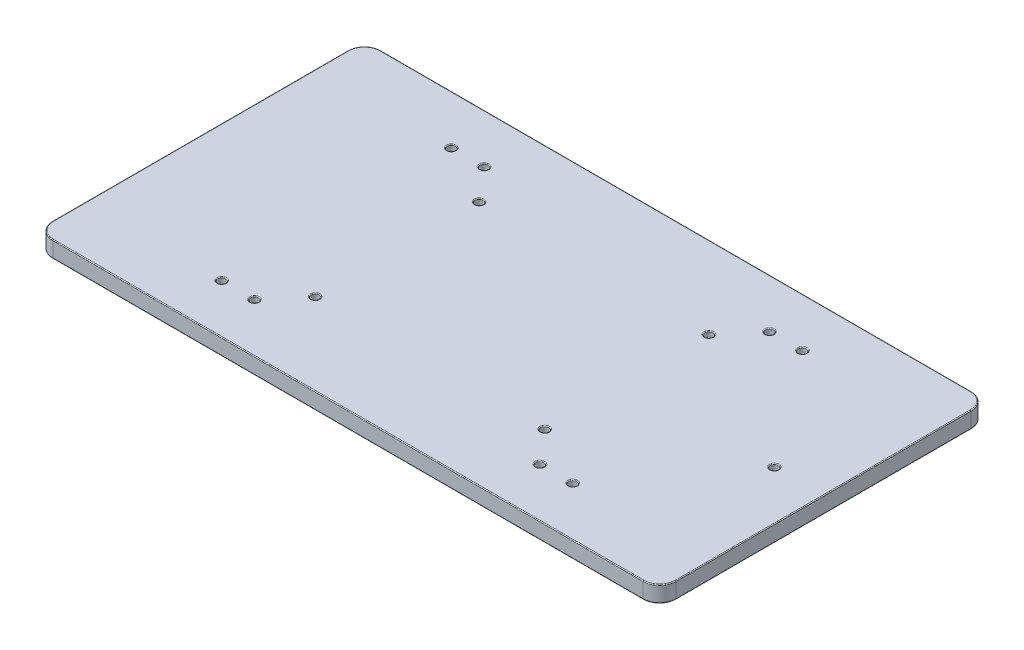
SolidWorks part; units mm, degrees
ref_plane "Front Plane" through (0, 0, 0) normal (0, 0, 1) x (1, 0, 0)
ref_plane "Top Plane" through (0, 0, 0) normal (0, 1, 0) x (1, 0, 0)
ref_plane "Right Plane" through (0, 0, 0) normal (1, 0, 0) x (0, 0, -1)
sketch "Sketch1" plane through (0, 0, 0) normal (0, 1, 0) x (1, 0, 0)
  line L0 (80, 50) -> (80, -50) construction
  line L1 (-95, -50) -> (95, -50)
  line L2 (-95, -50) -> (-95, 50)
  line L3 (-95, 50) -> (95, 50)
  line L4 (95, -50) -> (95, 50)
  line L5 (-95, -50) -> (95, 50) construction
  line L6 (-95, 50) -> (95, -50) construction
  line L7 (-35, -25) -> (35, -25) construction
  line L8 (-35, -25) -> (-35, 25) construction
  line L9 (-35, 25) -> (35, 25) construction
  line L10 (35, -25) -> (35, 25) construction
  line L11 (-35, -25) -> (35, 25) construction
  line L12 (-35, 25) -> (35, -25) construction
  line L13 (0, 0) -> (0, 22.0913) construction
  line L14 (0, 0) -> (47.0004, 0) construction
  circle A0 centre (35, 25) radius 1.25
  circle A1 centre (35, -25) radius 1.25
  circle A2 centre (-35, -25) radius 1.25
  circle A3 centre (-35, 25) radius 1.25
  circle A4 centre (80, 0) radius 1.25
  circle A5 centre (-53.5, -35) radius 1.25
  circle A6 centre (-43.5, -35) radius 1.25
  circle A7 centre (-43.5, 35) radius 1.25
  circle A8 centre (-53.5, 35) radius 1.25
  circle A9 centre (43.5, -35) radius 1.25
  circle A10 centre (53.5, -35) radius 1.25
  circle A11 centre (53.5, 35) radius 1.25
  circle A12 centre (43.5, 35) radius 1.25
  point P0 (0, 0)
  point P5 (0, 0)
  dimension "D5" = 2.5
  dimension "D7" = 2.5
  dimension "D8" = 2.5
  dimension "D1" = 190
  dimension "D2" = 100
  dimension "D3" = 70
  dimension "D4" = 50
  dimension "D6" = 15
  dimension "D9" = 10
  dimension "D10" = 43.5
  dimension "D11" = 15
  dimension "D12" = 15
extrude "Boss-Extrude1" add sketch "Sketch1" along normal blind 5
fillet "Fillet1" radius 5 4 edges at (-95, 2.5, -50) (-95, 2.5, 50) (95, 2.5, -50) (95, 2.5, 50)
fillet "Fillet2" radius 0.25 42 edges at (43.5, 0, -33.75) (53.5, 0, 33.75) (-53.5, 0, -36.25) (-43.5, 0, 36.25) (80, 0, 1.25) (-35, 0, 26.25) (35, 0, -23.75) (-93.5355, 0, 48.5355) (0, 0, 50) (93.5355, 0, 48.5355) (95, 0, 0) (93.5355, 0, -48.5355) (0, 0, -50) (-93.5355, 0, -48.5355) (-95, 0, 0) (35, 0, 26.25) (-35, 0, -23.75) (-53.5, 0, 36.25) (-43.5, 0, -36.25) (43.5, 0, 33.75) (53.5, 0, -33.75) (43.5, 5, -33.75) (53.5, 5, -33.75) (53.5, 5, 33.75) (43.5, 5, 33.75) (-53.5, 5, -36.25) (-43.5, 5, -36.25) (-43.5, 5, 36.25) (-53.5, 5, 36.25) (80, 5, 1.25) (-35, 5, -23.75) (-35, 5, 26.25) (35, 5, 26.25) (35, 5, -23.75) (93.5355, 5, -48.5355) (95, 5, 0) (93.5355, 5, 48.5355) (0, 5, 50) (-93.5355, 5, 48.5355) (-95, 5, 0) (-93.5355, 5, -48.5355) (0, 5, -50)
